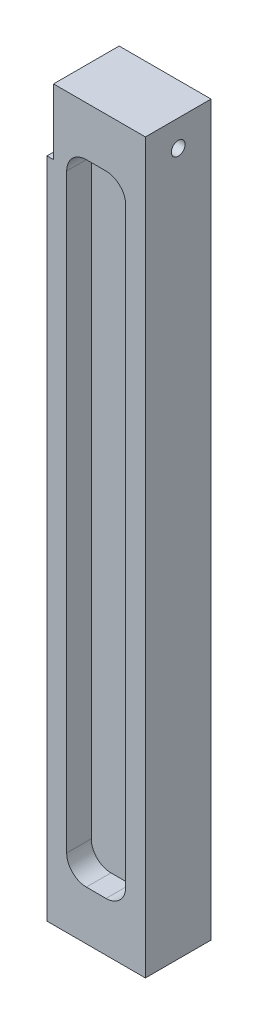
SolidWorks part; units mm, degrees
material "6061 合金"
ref_plane "前视基准面" through (0, 0, 0) normal (0, 0, 1) x (1, 0, 0)
ref_plane "上视基准面" through (0, 0, 0) normal (0, 1, 0) x (1, 0, 0)
ref_plane "右视基准面" through (0, 0, 0) normal (1, 0, 0) x (0, 0, -1)
sketch "草图1" plane through (0, 0, 0) normal (0, 1, 0) x (1, 0, 0)
  line L1 (-15, -10) -> (15, -10)
  line L2 (-15, -10) -> (-15, 10)
  line L3 (-15, 10) -> (15, 10)
  line L4 (15, -10) -> (15, 10)
  line L5 (-15, -10) -> (15, 10) construction
  line L6 (-15, 10) -> (15, -10) construction
  point P0 (0, 0)
  dimension "D1" = 20
  dimension "D2" = 30
extrude "凸台-拉伸1" add sketch "草图1" along normal blind 222
sketch "草图2" plane through (0, 0, -10) normal (0, 0, 1) x (1, 0, 0)
  line L0 (0, 0) -> (0, 211.9387) construction
  line L1 (-15, 0) -> (15, 0) construction
  line L2 (-3, 15) -> (3, 15)
  line L3 (-9, 21) -> (-9, 201)
  line L7 (-3, 207) -> (3, 207)
  line L8 (9, 21) -> (9, 201)
  line L9 (-9, 15) -> (9, 207) construction
  line L10 (-9, 207) -> (9, 15) construction
  line L11 (-15, 222) -> (15, 222) construction
  arc A0 (3, 15) -> (9, 21) centre (3, 21) ccw
  arc A1 (-3, 15) -> (-9, 21) centre (-3, 21) cw
  arc A2 (3, 207) -> (9, 201) centre (3, 201) cw
  arc A3 (-9, 201) -> (-3, 207) centre (-3, 201) cw
  point P3 (0, 111)
  dimension "D4" = 6
  dimension "D1" = 18
  dimension "D2" = 15
  dimension "D3" = 15
extrude "切除-拉伸1" cut sketch "草图2" along normal offset from surface (7.5 mm away) 2.5 up to plane "前视基准面"
mirror "镜向1" about plane through (0, 0, 0) normal (0, 0, 1) of "切除-拉伸1"
hole_wizard "M5 螺纹孔1" positions "草图4" profile "草图3" tap size "M5" standard "GB"
sketch "草图4" plane through (0, 0, 0) normal (0, -1, 0) x (-1, 0, 0)
  line L0 (0, 0) -> (0, 7.831) construction
  line L2 (-15, -10) -> (-15, 10) construction
  point P0 (8, 0)
  point P2 (-8, 0)
  dimension "D1" = 7
sketch "草图3" plane through (-8, 0, 0) normal (1, 0, 0) x (0, 0, -1)
  line L0 (0, 0) -> (0, 15.2618)
  line L1 (0, 15.2618) -> (2.1, 14)
  line L2 (2.1, 14) -> (2.1, 0)
  line L5 (2.1, 0) -> (0, 0)
  line L10 (0, 15.2618) -> (-2.1, 14) construction
  line L11 (0, -6.35) -> (0, 107.95) construction
  dimension "螺纹孔钻头直径" = 4.2
  dimension "螺纹孔钻头深度" = 14
  dimension "导头角度" = 118
cosmetic thread "孔螺蚊线1" parameters "D1"=10, "D2"=5
cosmetic thread "孔螺蚊线2" parameters "D1"=10, "D2"=5
hole_wizard "M5 螺纹孔2" positions "草图6" profile "草图5" tap size "M5" standard "GB" end condition up to next
sketch "草图6" plane through (15, 0, 0) normal (1, 0, 0) x (0, 0, -1)
  line L0 (-10, 222) -> (10, 222) construction
  point P0 (0, 214)
  dimension "D1" = 8
sketch "草图5" plane through (15, 214, 0) normal (0, 1, 0) x (0, 0, -1)
  line L0 (0, 0) -> (0, 30)
  line L1 (0, 30) -> (2.1, 30)
  line L2 (2.1, 30) -> (2.1, 0)
  line L5 (2.1, 0) -> (0, 0)
  line L11 (0, -6.35) -> (0, 107.95) construction
  dimension "通孔螺纹孔钻头直径" = 4.2
  dimension "通孔螺纹孔钻头深度" = 30
cosmetic thread "孔螺蚊线3" parameters "D2"=5
sketch "草图7" plane through (0, 0, 10) normal (0, 0, -1) x (-1, 0, 0)
  line L0 (13, 222) -> (13, 202)
  line L1 (-15, 222) -> (15, 222) construction
  line L2 (13, 202) -> (15, 202)
  line L4 (15, 222) -> (15, 0) construction
  dimension "D1" = 2
  dimension "D2" = 20
extrude "切除-拉伸2" cut sketch "草图7" along normal through all
hole_wizard "M4 螺纹孔1" positions "草图9" profile "草图8" tap size "M4" standard "GB"
sketch "草图9" plane through (0, 0, 2.5) normal (0, 0, 1) x (1, 0, 0)
  line L0 (-15, 0) -> (15, 0) construction
  point P0 (0, 85)
  dimension "D1" = 85
sketch "草图8" plane through (0, 85, 2.5) normal (1, 0, 0) x (0, -1, 0)
  line L0 (0, 0) -> (0, 5)
  line L1 (0, 5) -> (1.65, 5)
  line L2 (1.65, 5) -> (1.65, 0)
  line L5 (1.65, 0) -> (0, 0)
  line L11 (0, -6.35) -> (0, 107.95) construction
  dimension "螺纹线主直径" = 3.3
  dimension "通孔螺纹孔钻头深度" = 5
